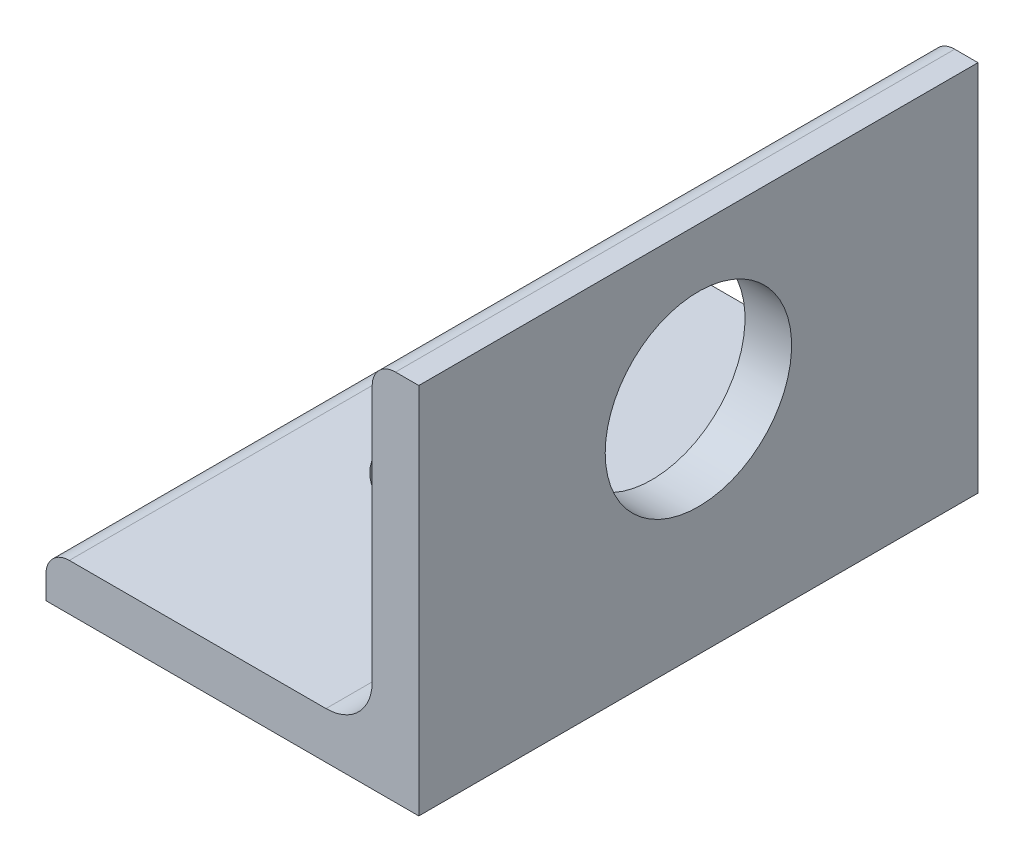
SolidWorks part; units mm, degrees
ref_plane "Front Plane" through (0, 0, 0) normal (0, 0, 1) x (1, 0, 0)
ref_plane "Top Plane" through (0, 0, 0) normal (0, 1, 0) x (1, 0, 0)
ref_plane "Right Plane" through (0, 0, 0) normal (1, 0, 0) x (0, 0, -1)
sketch "Sketch2" plane through (0, 0, 0) normal (0, 0, 1) x (1, 0, 0)
  line L0 (-6.35, 0) -> (6.35, 0)
  line L1 (6.35, 0) -> (6.35, 12.7)
  line L2 (6.35, 12.7) -> (4.7625, 12.7) construction
  line L3 (4.7625, 11.9062) -> (4.7625, 3.1623)
  line L4 (3.1877, 1.5875) -> (-5.5563, 1.5875)
  line L5 (-6.35, 0) -> (-6.35, 1.5875) construction
  line L6 (5.5563, 12.7) -> (6.35, 12.7)
  line L7 (-6.35, 0.7937) -> (-6.35, 0)
  arc A0 (4.7625, 11.9062) -> (5.5563, 12.7) centre (5.5563, 11.9062) cw
  arc A1 (-6.35, 0.7937) -> (-5.5563, 1.5875) centre (-5.5563, 0.7937) cw
  arc A2 (4.7625, 3.1623) -> (3.1877, 1.5875) centre (3.1877, 3.1623) cw
  dimension "Inside Radius" = 1.5748
  dimension "Vert" = 12.7
  dimension "Horz" = 12.7
  dimension "Thickness" = 1.5875
extrude "Boss-Extrude1" add sketch "Sketch2" along normal mid plane 19.05
sketch "Break Locations" plane through (0, 0, 0) normal (1, 0, 0) x (0, 0, -1)
  line L1 (-9.525, 0) -> (-9.525, 12.7) construction
  line L2 (9.525, 0) -> (9.525, 12.7) construction
  point P0 (1.27, 0)
  point P1 (-1.27, 0)
  dimension "D1" = 10.795
  dimension "D2" = 10.795
ref_plane "Contact Plane 1" through (0, 1.5875, 0) normal (0, 1, 0) x (1, 0, 0)
ref_plane "Contact Plane 2" through (4.7625, 0, 0) normal (-1, 0, 0) x (0, 0, 1)
sketch "Sketch3" plane through (0, 1.5875, 0) normal (0, 1, 0) x (1, 0, 0)
  line L0 (3.1877, -9.525) -> (-5.5563, -9.525) construction
  line L1 (3.1877, -9.525) -> (3.1877, 9.525) construction
  point P0 (-1.1843, 0)
  point P3 (-1.1843, -9.525)
  point P4 (-1.1843, -9.525)
  point P5 (-1.1843, -9.525)
  point P6 (-1.1843, -9.525)
  point P7 (-1.1843, 4.3047)
  point P8 (-1.1843, 0.2668)
  point P11 (3.1877, 0)
hole_wizard "#6 (0.204) Diameter Hole1" positions "Sketch8" profile "Sketch9" hole size "#6" standard "ANSI Inch" end condition through all
sketch "Sketch8" plane through (0, 1.5875, 0) normal (0, 1, 0) x (1, 0, 0)
  line L0 (3.1877, -9.525) -> (-5.5563, -9.525) construction
  line L1 (3.1877, -9.525) -> (3.1877, 9.525) construction
  point P0 (-1.1843, 0)
  point P3 (0, 0)
  point P7 (-1.1843, -9.525)
  point P10 (3.1877, 0)
sketch "Sketch9" plane through (-1.1843, 1.5875, 0) normal (1, 0, 0) x (0, 0, 1)
  line L0 (0, 0) -> (0, 1.5875)
  line L1 (0, 1.5875) -> (2.5908, 1.5875)
  line L2 (2.5908, 1.5875) -> (2.5908, 0)
  line L5 (2.5908, 0) -> (0, 0)
  line L11 (0, -6.35) -> (0, 107.95) construction
  dimension "Thru Hole Dia." = 5.1816
  dimension "Thru Hole Depth" = 1.5875
sketch "Sketch10" plane through (4.7625, 0, 0) normal (-1, 0, 0) x (0, 0, 1)
  line L0 (9.525, 11.9062) -> (-9.525, 11.9062) construction
  line L1 (9.525, 11.9062) -> (9.525, 3.1623) construction
  point P0 (0, 7.5343)
  point P3 (0, 11.9062)
  point P4 (0, 7.5859)
  point P7 (9.525, 7.5343)
hole_wizard "1/4 (0.25) Diameter Hole1" positions "Sketch11" profile "Sketch12" hole size "1/4" standard "ANSI Inch" end condition through all
sketch "Sketch11" plane through (4.7625, 0, 0) normal (-1, 0, 0) x (0, 0, 1)
  line L0 (9.525, 11.9062) -> (9.525, 3.1623) construction
  line L1 (9.525, 11.9062) -> (-9.525, 11.9062) construction
  point P0 (0, 7.5343)
  point P5 (9.525, 7.5343)
  point P8 (0, 11.9062)
sketch "Sketch12" plane through (4.7625, 7.5343, 0) normal (0, 1, 0) x (0, 0, 1)
  line L0 (0, 0) -> (0, 1.5875)
  line L1 (0, 1.5875) -> (3.175, 1.5875)
  line L2 (3.175, 1.5875) -> (3.175, 0)
  line L5 (3.175, 0) -> (0, 0)
  line L11 (0, -6.35) -> (0, 107.95) construction
  dimension "Thru Hole Dia." = 6.35
  dimension "Thru Hole Depth" = 1.5875
equation "\"D1@Break Locations\"=.85*\"Vert@Sketch2\""
equation "\"D2@Break Locations\"=\"D1@Break Locations\""
